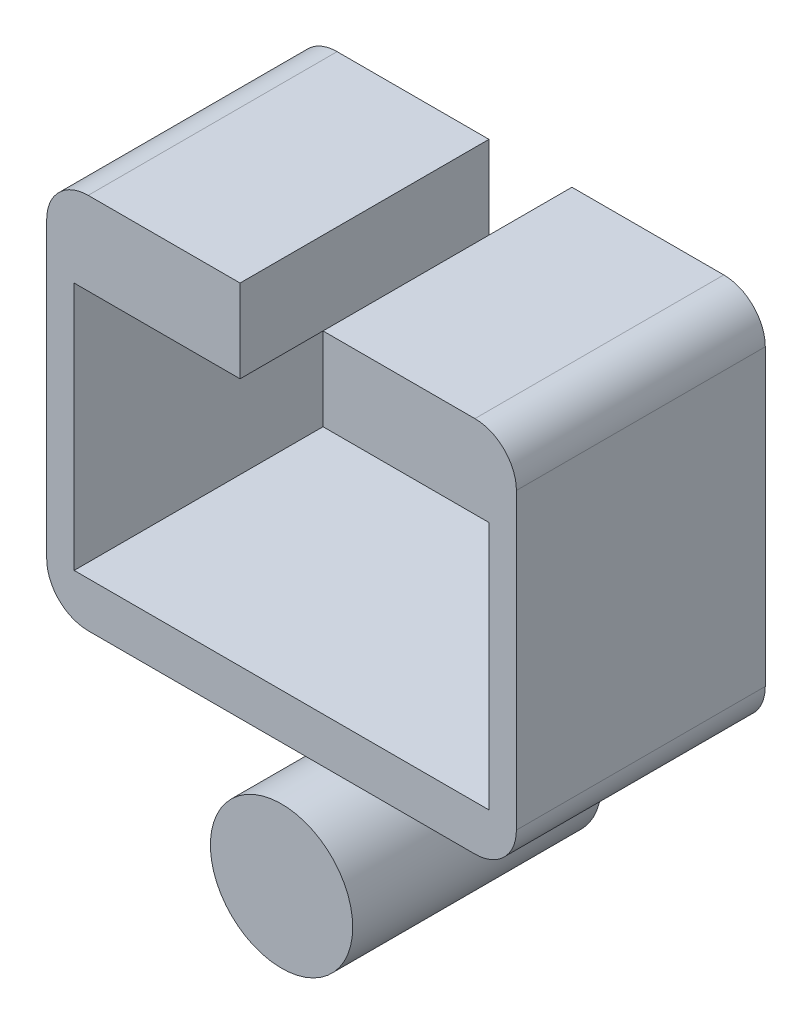
SolidWorks part; units mm, degrees
material "A36 Steel"
ref_plane "Front Plane" through (0, 0, 0) normal (0, 0, 1) x (1, 0, 0)
ref_plane "Top Plane" through (0, 0, 0) normal (0, 1, 0) x (1, 0, 0)
ref_plane "Right Plane" through (0, 0, 0) normal (1, 0, 0) x (0, 0, -1)
sketch "Sketch1" plane through (0, 0, 0) normal (0, 0, 1) x (1, 0, 0)
  circle A0 centre (0, 0) radius 10.895
  dimension "D1" = 21.7901
extrude "Boss-Extrude1" add sketch "Sketch1" against normal blind 38.1
sketch "Sketch2" plane through (0, 0, -38.1) normal (0, 0, -1) x (-1, 0, 0)
  line L0 (-11.176, 0) -> (11.176, 0)
  line L3 (-11.176, 19.05) -> (11.176, 19.05)
  line L4 (-11.176, 19.05) -> (-22.6044, 19.05)
  line L5 (11.176, 19.05) -> (22.6044, 19.05)
  line L6 (-22.6044, 19.05) -> (-11.176, 0)
  line L7 (22.6044, 19.05) -> (11.176, 0)
  point P5 (0, 0)
  dimension "D1" = 22.352
  dimension "D2" = 19.05
extrude "Boss-Extrude2" add sketch "Sketch2" against normal blind 8.89
sketch "Sketch3" plane through (0, 0, -38.1) normal (0, 0, -1) x (-1, 0, 0)
  line L0 (-31.75, 19.05) -> (31.75, 19.05)
  line L2 (22.6044, 19.05) -> (-22.6044, 19.05) construction
  line L3 (-31.75, 19.05) -> (-31.75, 25.9773)
  line L4 (31.75, 19.05) -> (31.75, 25.9773)
  line L5 (-31.75, 25.9773) -> (31.75, 25.9773)
  point P3 (0, 19.05)
  dimension "D1" = 63.5
  dimension "D2" = 6.9273
extrude "Boss-Extrude3" add sketch "Sketch3" against normal blind 38.1
sketch "Sketch4" plane through (0, 0, -38.1) normal (0, 0, -1) x (-1, 0, 0)
  line L0 (-31.75, 25.9773) -> (-31.75, 64.0773)
  line L1 (-31.75, 64.0773) -> (-6.35, 64.0773)
  line L2 (-6.35, 64.0773) -> (-6.35, 76.7773)
  line L3 (31.75, 25.9773) -> (31.75, 64.0773)
  line L4 (31.75, 64.0773) -> (6.35, 64.0773)
  line L5 (6.35, 64.0773) -> (6.35, 76.7773)
  line L6 (6.35, 76.7773) -> (35.9483, 76.7773)
  line L7 (35.9483, 76.7773) -> (35.9483, 19.05)
  line L8 (31.75, 19.05) -> (35.9483, 19.05)
  line L9 (-31.75, 19.05) -> (-35.9483, 19.05)
  line L10 (-6.35, 76.7773) -> (-35.9483, 76.7773)
  line L11 (-35.9483, 19.05) -> (-35.9483, 76.7773)
  line L12 (-31.75, 19.05) -> (-31.75, 25.9773)
  line L13 (31.75, 19.05) -> (31.75, 25.9773)
  dimension "D4" = 38.1
  dimension "D2" = 12.7
  dimension "D3" = 4.1983
  dimension "D1" = 25.4
extrude "Boss-Extrude4" add sketch "Sketch4" against normal blind 38.1
ref_plane "Plane2" through (0, 10.895, 0) normal (0, 1, 0) x (1, 0, 0)
fillet "Fillet1" radius 6.35 4 edges at (35.9483, 19.05, -19.05) (35.9483, 76.7773, -19.05) (-35.9483, 19.05, -19.05) (-35.9483, 76.7773, -19.05)
sketch "Sketch7" plane through (35.9483, 0, 0) normal (1, 0, 0) x (0, 0, -1)
  line L0 (38.1, 70.4273) -> (38.1, 25.4) construction
  line L1 (8.89, 64.0773) -> (29.21, 64.0773)
  line L2 (8.89, 64.0773) -> (8.89, 30.48)
  line L3 (8.89, 30.48) -> (29.21, 30.48)
  line L4 (29.21, 64.0773) -> (29.21, 30.48)
  line L5 (0, 70.4273) -> (0, 25.4) construction
  line L6 (0, 25.4) -> (38.1, 25.4) construction
  line L7 (38.1, 70.4273) -> (0, 70.4273) construction
  dimension "D1" = 8.89
  dimension "D2" = 8.89
  dimension "D3" = 5.08
  dimension "D4" = 6.35
equation "\"F_1\"= 750"
equation "\"Sy\"= 36300"
equation "\"E\"= 29000000"
equation "\"N\"= 4"
equation "\"L_a\"= 1.5"
equation "\"W_b\"= 0.88"
equation "\"L_b\"= 0.75"
equation "\"F_2\"= 375"
equation "\"L\"=1.5"
equation "\"B_c\"= 2.5"
equation "\"H_d\"= 1.5"
equation "\"S_allow\"= \"Sy\" / \"N\""
equation "\"B_e\"= 1"
equation "\"M_a\"= \"F_1\" * ( \"L_a\" / 2 )"
equation "\"M_c\"= ( \"F_1\" * \"L\" ) / 4"
equation "\"M_d\"= \"F_2\" * \"L\""
equation "\"M_e\"= \"F_2\" * \"L\""
equation "\"d_a\"= ( ( 32 * \"M_a\" ) / ( PI * \"S_allow\" ) ) ^ ( 1 / 3 )"
equation "\"T_b\"= \"F_1\" / ( \"d_a\" * \"S_allow\" )"
equation "\"H_c\"= sqr ( ( 6 * \"M_c\" ) / ( \"B_c\" * \"S_allow\" ) )"
equation "\"B_d\"= ( 6 * \"M_d\" ) / ( ( \"H_d\" ) ^ 2 * \"S_allow\" )"
equation "\"H_e\"= sqr ( ( 6 * \"M_e\" ) / ( \"B_e\" * \"S_allow\" ) )"
equation "\"D1@Sketch1\"=\"d_a\""
equation "\"D1@Boss-Extrude1\"=\"L_a\""
equation "\"D2@Sketch2\"=\"L_b\""
equation "\"D1@Sketch2\"=\"W_b\""
equation "\"D1@Boss-Extrude2\"=\"T_b\""
equation "\"D1@Sketch3\"=\"B_c\""
equation "\"D2@Sketch3\"=\"H_c\""
equation "\"D1@Boss-Extrude3\"=\"L\""
equation "\"D1@Sketch4\"=\"B_e\""
equation "\"D3@Sketch4\"=\"B_d\""
equation "\"D4@Sketch4\"=\"H_d\""
equation "\"D1@Boss-Extrude4\"=\"L\""
